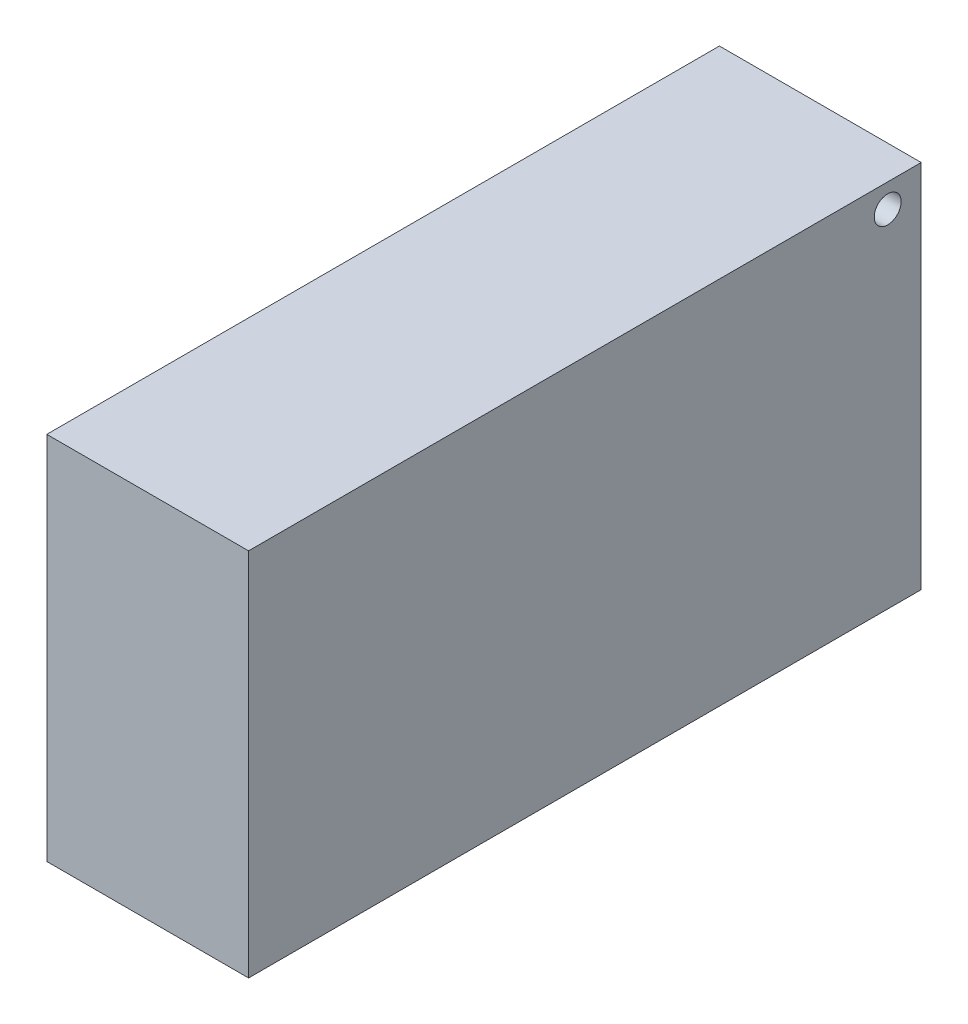
SolidWorks part; units mm, degrees
ref_plane "Спереди" through (0, 0, 0) normal (0, 0, 1) x (1, 0, 0)
ref_plane "Сверху" through (0, 0, 0) normal (0, 1, 0) x (1, 0, 0)
ref_plane "Справа" through (0, 0, 0) normal (1, 0, 0) x (0, 0, -1)
sketch "Эскиз1" plane through (0, 0, 0) normal (1, 0, 0) x (0, 0, -1)
  line L1 (211.9938, 108.0907) -> (11.9938, 108.0907)
  line L2 (211.9938, 108.0907) -> (211.9938, -1.9093)
  line L3 (211.9938, -1.9093) -> (11.9938, -1.9093)
  line L4 (11.9938, 108.0907) -> (11.9938, -1.9093)
  point P4 (-3.6684, 108.0907)
  point P5 (0, 0)
  dimension "D1" = 200
  dimension "D2" = 110
extrude "Бобышка-Вытянуть1" add sketch "Эскиз1" along normal blind 60
sketch "Эскиз3" plane through (60, 0, 0) normal (1, 0, 0) x (0, 0, -1)
  circle A0 centre (202.0339, 101.0161) radius 4
extrude "Вырез-Вытянуть2" cut sketch "Эскиз3" against normal blind 20
